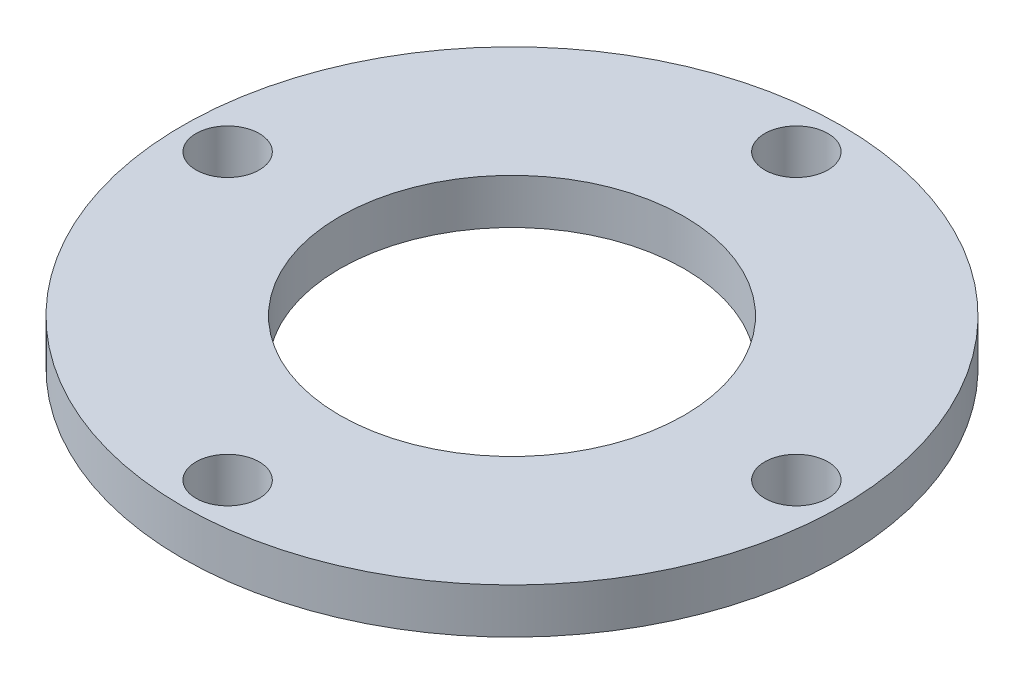
SolidWorks part; units mm, degrees
material "2024 Alloy"
ref_plane "Front Plane" through (0, 0, 0) normal (0, 0, 1) x (1, 0, 0)
ref_plane "Top Plane" through (0, 0, 0) normal (0, 1, 0) x (1, 0, 0)
ref_plane "Right Plane" through (0, 0, 0) normal (1, 0, 0) x (0, 0, -1)
sketch "Sketch1" plane through (0, 0, 0) normal (0, 1, 0) x (1, 0, 0)
  circle A0 centre (0, 0) radius 10.9375
  circle A1 centre (0, 0) radius 5.715
  circle A2 centre (0, 0) radius 9.4375 construction
  circle A3 centre (0, 9.4375) radius 1.05
  circle A4 centre (9.4375, 0) radius 1.05
  circle A5 centre (0, -9.4375) radius 1.05
  circle A6 centre (-9.4375, 0) radius 1.05
  dimension "D1" = 11.43
  dimension "D2" = 21.875
  dimension "D3" = 1.5
  dimension "D4" = 2.1
extrude "Boss-Extrude1" add sketch "Sketch1" along normal blind 1.5
